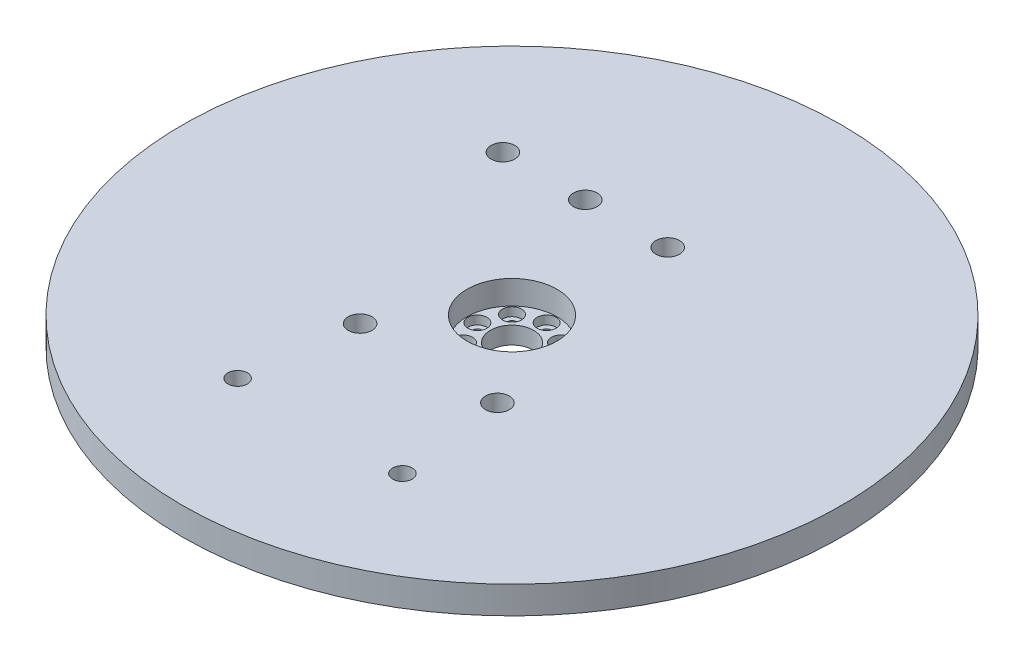
SolidWorks part; units mm, degrees
other "Markup1"
sketch "Sketch21" plane through (-65.5, -15.05, -60) normal (-0.0927, -0.2854, -0.9539) x (0.9951, -0.0609, -0.0785)
material "6061 Alloy"
ref_plane "Front Plane" through (0, 0, 0) normal (0, 0, 1) x (1, 0, 0)
ref_plane "Top Plane" through (0, 0, 0) normal (0, 1, 0) x (1, 0, 0)
ref_plane "Right Plane" through (0, 0, 0) normal (1, 0, 0) x (0, 0, -1)
sketch "Sketch1" plane through (0, 0, 0) normal (0, 1, 0) x (1, 0, 0)
  circle A0 centre (0, 0) radius 76.2
  dimension "D1" = 152.4
extrude "Boss-Extrude1" add sketch "Sketch1" along normal mid plane 6.35
sketch "Sketch2" plane through (0, -3.175, 0) normal (0, -1, 0) x (1, 0, 0)
  circle A0 centre (0, 0) radius 12.065
  circle A1 centre (0, 0) radius 76.2 construction
  dimension "D1" = 24.13
extrude "Boss-Extrude2" add sketch "Sketch2" along normal blind 3.175
sketch "Sketch5" plane through (0, 3.175, 0) normal (0, 1, 0) x (1, 0, 0)
  circle A0 centre (0, 0) radius 10.4
  circle A1 centre (0, 0) radius 76.2 construction
  dimension "D1" = 20.8
extrude "Cut-Extrude1" cut sketch "Sketch5" against normal offset from surface (5.525 mm away) 4 up to face at (0, -6.35, -12.065)
sketch "Sketch6" plane through (0, -2.35, 0) normal (0, 1, 0) x (1, 0, 0)
  circle A0 centre (0, 0) radius 5
  circle A1 centre (0, 0) radius 10.4 construction
  dimension "D1" = 10
extrude "Cut-Extrude2" cut sketch "Sketch6" along direction (0, -1, 0) on the side against the normal up to next (4 mm away)
sketch "Sketch15" plane through (0, -6.35, 0) normal (0, 1, 0) x (1, 0, 0)
  circle A0 centre (0, 8) radius 1
  circle A1 centre (-5.6569, 5.6569) radius 1
  circle A2 centre (5.6569, 5.6569) radius 1
  circle A3 centre (-5.6569, -5.6569) radius 1
  circle A4 centre (5.6569, -5.6569) radius 1
  circle A5 centre (-8, 0) radius 1
  circle A6 centre (0, -8) radius 1
  circle A7 centre (8, 0) radius 1
  circle A8 centre (0, 0) radius 4
  circle A9 centre (0, 0) radius 11
  circle A10 centre (0, 0) radius 2.25
  circle A11 centre (0, 0) radius 5
  circle A12 centre (0, 0) radius 5 construction
  dimension "D1" = 4.5
  dimension "D2" = 8
  dimension "D3" = 10
  dimension "D4" = 22
  dimension "D5" = 2
  dimension "D6" = 8
  dimension "D7" = 5.6569
  dimension "D8" = 8
  dimension "D9" = 5.6569
  dimension "D10" = 5.6569
  dimension "D11" = 8
  dimension "D12" = 5.6569
  dimension "D13" = 8
hole_wizard "CBORE for M2 SHCS1" positions "Sketch19" profile "Sketch20" counterbore size "M2" standard "ANSI Metric"
sketch "Sketch19" plane through (0, -2.35, 0) normal (0, 1, 0) x (1, 0, 0)
  point P0 (-5.6569, 5.6569)
  point P3 (0, 8)
  point P6 (5.6569, 5.6569)
  point P9 (8, 0)
  point P12 (5.6569, -5.6569)
  point P15 (0, -8)
  point P18 (-5.6569, -5.6569)
  point P21 (-8, 0)
sketch "Sketch20" plane through (-5.6569, -2.35, -5.6569) normal (1, 0, 0) x (0, 0, 1)
  line L0 (0, 0) -> (0, 6.6609)
  line L1 (0, 6.6609) -> (1.1, 6)
  line L2 (1.1, 6) -> (1.1, 2)
  line L3 (1.1, 2) -> (2.2, 2)
  line L4 (2.2, 2) -> (2.2, 0)
  line L5 (2.2, 0) -> (0, 0)
  line L10 (0, 6.6609) -> (-1.1, 6) construction
  line L11 (0, -6.35) -> (0, 107.95) construction
  dimension "Hole Dia." = 2.2
  dimension "Hole Depth" = 6
  dimension "C'Bore Dia." = 4.4
  dimension "C'Bore Depth" = 2
  dimension "Drill Angle" = 118
hole_wizard "M4 Clearance Hole1" positions "Sketch22" profile "Sketch23" hole size "M4" standard "ANSI Metric" end condition through all
sketch "Sketch22" plane through (0, 3.175, 0) normal (0, 1, 0) x (1, 0, 0)
  point P0 (19.05, -44.3882)
  point P3 (-19.05, -44.3882)
sketch "Sketch23" plane through (19.05, 3.175, 44.3882) normal (1, 0, 0) x (0, 0, 1)
  line L0 (0, 0) -> (0, 9.525)
  line L1 (0, 9.525) -> (2.25, 9.525)
  line L2 (2.25, 9.525) -> (2.25, 0)
  line L5 (2.25, 0) -> (0, 0)
  line L11 (0, -6.35) -> (0, 107.95) construction
  dimension "Thru Hole Dia." = 4.5
  dimension "Thru Hole Depth" = 9.525
hole_wizard "M5 Clearance Hole1" positions "Sketch24" profile "Sketch25" hole size "M5" standard "ANSI Metric" end condition through all
sketch "Sketch24" plane through (0, 3.175, 0) normal (0, 1, 0) x (1, 0, 0)
  point P0 (-33.6688, 31.5674)
  point P3 (-14.6188, 31.5674)
  point P6 (4.4312, 31.5674)
  point P9 (-15.875, -19.2497)
  point P12 (15.875, -19.2497)
sketch "Sketch25" plane through (-33.6688, 3.175, -31.5674) normal (1, 0, 0) x (0, 0, 1)
  line L0 (0, 0) -> (0, 9.525)
  line L1 (0, 9.525) -> (2.75, 9.525)
  line L2 (2.75, 9.525) -> (2.75, 0)
  line L5 (2.75, 0) -> (0, 0)
  line L11 (0, -6.35) -> (0, 107.95) construction
  dimension "Thru Hole Dia." = 5.5
  dimension "Thru Hole Depth" = 9.525
